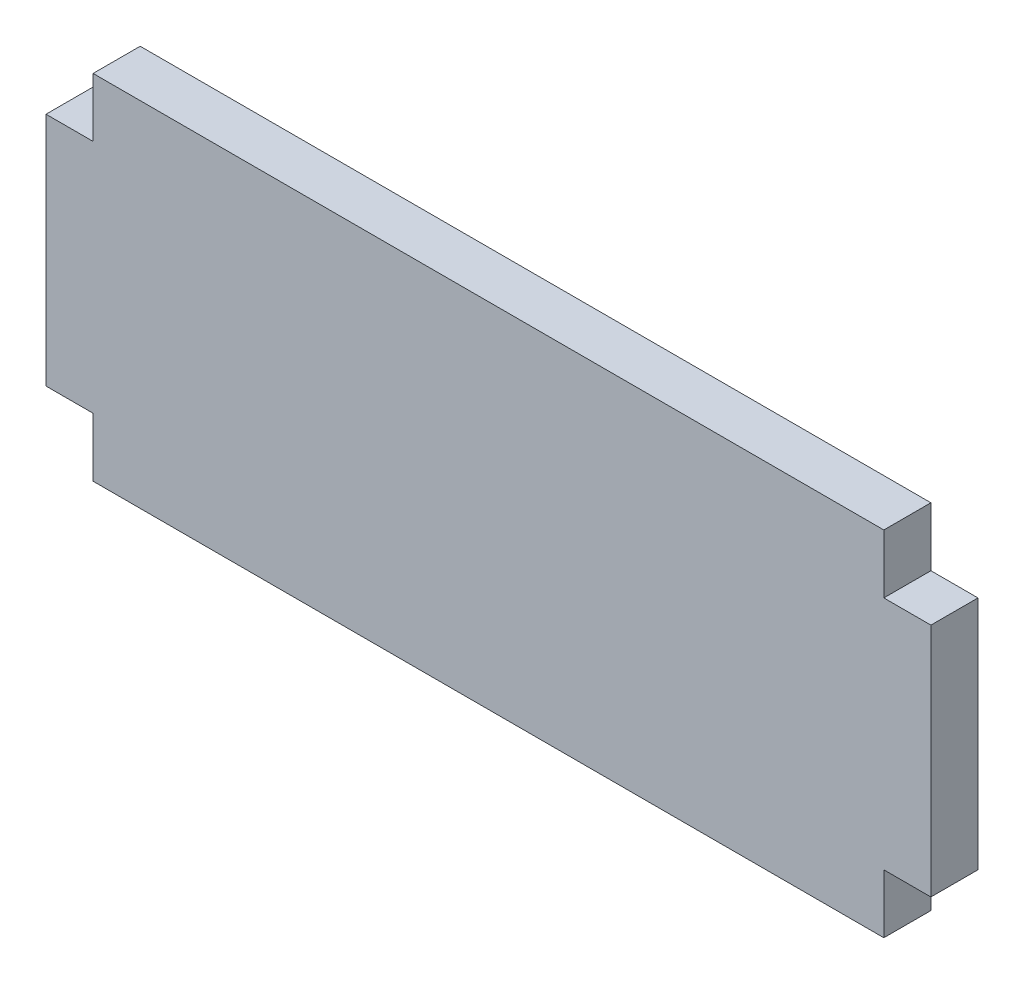
SolidWorks part; units mm, degrees
ref_plane "Front Plane" through (0, 0, 0) normal (0, 0, 1) x (1, 0, 0)
ref_plane "Top Plane" through (0, 0, 0) normal (0, 1, 0) x (1, 0, 0)
ref_plane "Right Plane" through (0, 0, 0) normal (1, 0, 0) x (0, 0, -1)
sketch "Sketch1" plane through (0, 0, 0) normal (0, 0, 1) x (1, 0, 0)
  line L0 (0, 9) -> (0, -9)
  line L1 (20.15, 9) -> (-20.15, 9)
  line L2 (20.15, 9) -> (20.15, -9)
  line L3 (20.15, -9) -> (-20.15, -9)
  line L4 (-20.15, 9) -> (-20.15, -9)
  line L5 (20.15, 9) -> (-20.15, -9) construction
  line L6 (20.15, -9) -> (-20.15, 9) construction
  line L7 (-20.15, 6) -> (-22.55, 6)
  line L9 (-20.15, -6) -> (-22.55, -6)
  line L10 (-22.55, 6) -> (-22.55, -6)
  line L11 (-20.15, 0) -> (-22.55, -6) construction
  line L12 (-20.15, 0) -> (-22.55, 6) construction
  line L13 (20.15, -6) -> (22.55, -6)
  line L14 (22.55, 6) -> (22.55, -6)
  line L15 (20.15, 6) -> (22.55, 6)
  line L16 (-22.55, 0) -> (-20.15, 0)
  point P0 (0, 0)
  point P6 (-20.15, 0)
extrude "Boss-Extrude1" add sketch "Sketch1" along normal blind 2.4 contours L7 L10 L9 L4 | L1 L4 L3 L0 | L3 L2 L1 L0 | L15 L2 L13 L14 | L16 L10 L9 L4
